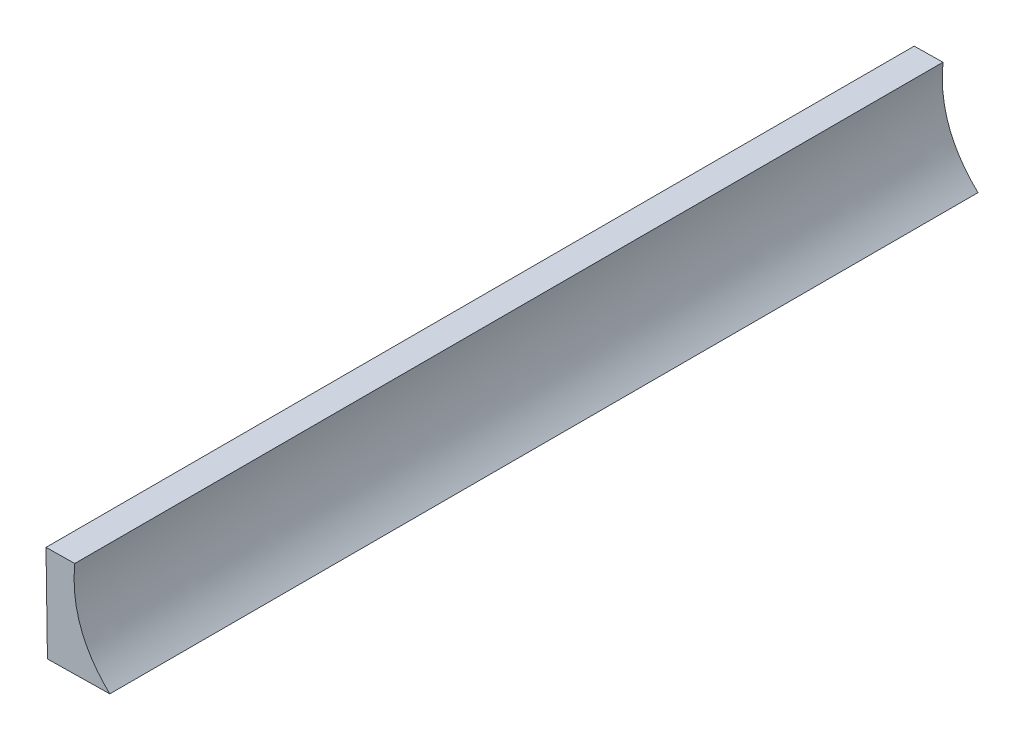
SolidWorks part; units mm, degrees
ref_plane "Plan de face" through (0, 0, 0) normal (0, 0, 1) x (1, 0, 0)
ref_plane "Plan de dessus" through (0, 0, 0) normal (0, 1, 0) x (1, 0, 0)
ref_plane "Plan de droite" through (0, 0, 0) normal (1, 0, 0) x (0, 0, -1)
sketch "Esquisse1" plane through (0, 0, 0) normal (0, 0, 1) x (1, 0, 0)
  line L0 (-55.5128, 21.3702) -> (-49.5128, 21.4605)
  line L1 (-55.2119, 1.3702) -> (-42.2119, 1.5658)
  line L2 (-55.5128, 21.3702) -> (-55.2119, 1.3702)
  spline S0 degree 2 poles (-49.5128, 21.4605) (-50.7101, 9.6214) (-42.2119, 1.5658) knots 0 0 0 1 1 1
  dimension "D1" = 6
  dimension "D2" = 13
  dimension "D3" = 20
extrude "Boss.-Extru.1" add sketch "Esquisse1" along normal blind 181 contours L2 L1 S0 L0
